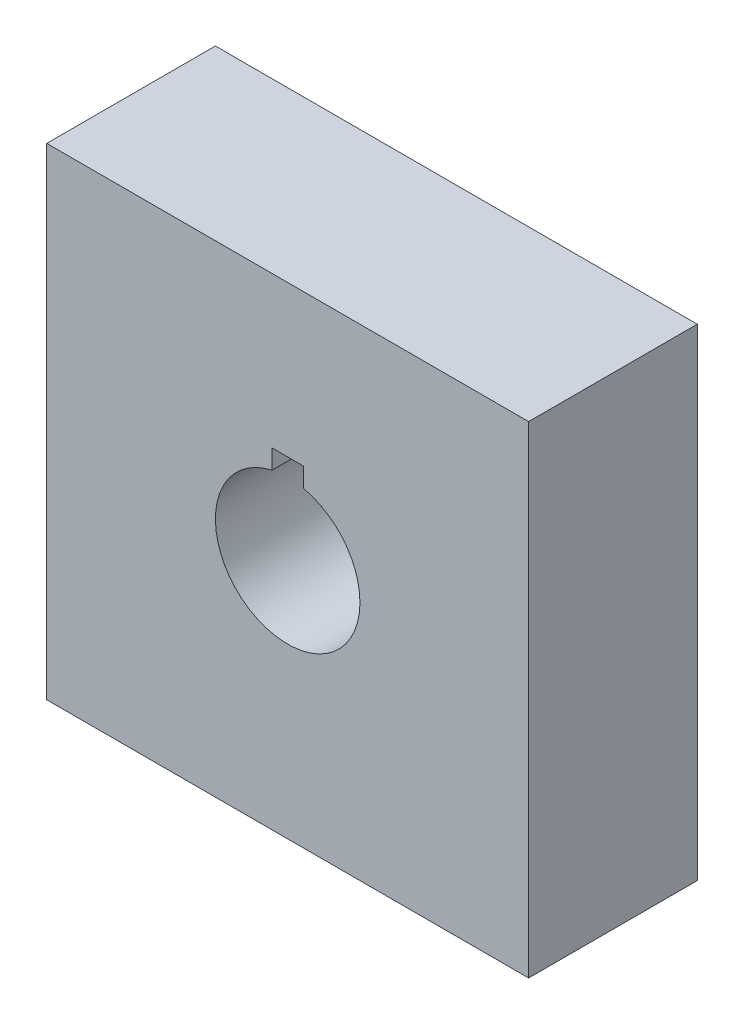
SolidWorks part; units mm, degrees
ref_plane "Front Plane" through (0, 0, 0) normal (0, 0, 1) x (1, 0, 0)
ref_plane "Top Plane" through (0, 0, 0) normal (0, 1, 0) x (1, 0, 0)
ref_plane "Right Plane" through (0, 0, 0) normal (1, 0, 0) x (0, 0, -1)
sketch "Sketch1" plane through (0, 0, 0) normal (0, 0, 1) x (1, 0, 0)
  line L0 (24.651, 50) -> (50, 50)
  line L5 (24.651, 50) -> (-50, 50)
  line L6 (-50, 50) -> (-50, -50)
  line L7 (-50, -50) -> (50, -50)
  line L8 (50, -50) -> (50, 50)
  dimension "D1" = 50
  dimension "D2" = 50
  dimension "D3" = 50
  dimension "D4" = 50
extrude "Boss-Extrude1" add sketch "Sketch1" along normal blind 35
sketch "Sketch2" plane through (0, 0, 35) normal (0, 0, 1) x (1, 0, 0)
  line L0 (0, -39.4749) -> (0, 71.9571) construction
  line L1 (-57.7461, 0) -> (75.7918, 0) construction
  line L2 (0, 18.647) -> (3.235, 18.647) construction
  line L3 (0, 18.647) -> (-3.235, 18.647) construction
  line L4 (-3.235, 18.647) -> (3.235, 18.647)
  line L5 (3.235, 18.647) -> (3.235, 14.647)
  line L6 (-3.235, 18.647) -> (-3.235, 14.647)
  circle A4 centre (0, 0) radius 15
  point P7 (0, 15)
  dimension "D2" = 30
  dimension "D3" = 4
  dimension "D4" = 3.235
  dimension "D1" = 3.235
extrude "Cut-Extrude1" cut sketch "Sketch2" against normal blind 50 contours A4 | A4 L5 L4 L6
